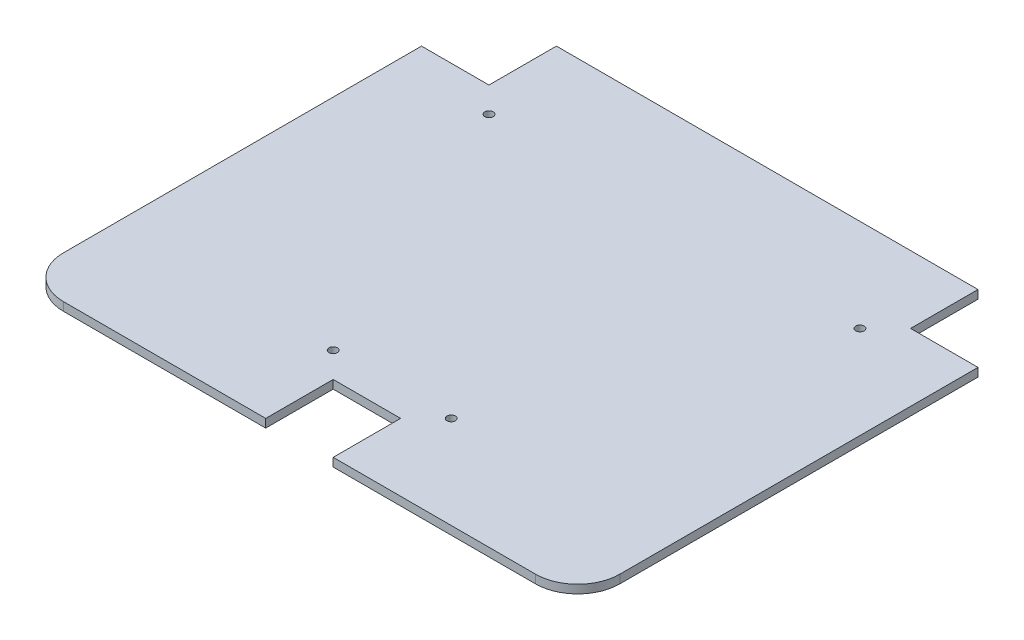
SolidWorks part; units mm, degrees
ref_plane "Plano frontal" through (0, 0, 0) normal (0, 0, 1) x (1, 0, 0)
ref_plane "Plano superior" through (0, 0, 0) normal (0, 1, 0) x (1, 0, 0)
ref_plane "Plano direito" through (0, 0, 0) normal (1, 0, 0) x (0, 0, -1)
sketch "Esboço1" plane through (0, 0, 0) normal (0, 1, 0) x (1, 0, 0)
  line L0 (516.2674, -155.797) -> (396.2674, -155.797)
  line L1 (371.2674, -130.797) -> (371.2674, 81.5882)
  line L2 (411.2674, 121.5882) -> (661.2674, 121.5882)
  line L3 (701.2674, -155.797) -> (411.2674, 81.5882) construction
  line L4 (371.2674, -155.797) -> (661.2674, 81.5882) construction
  line L5 (661.2674, 121.5882) -> (661.2674, 81.5882)
  line L6 (661.2674, 81.5882) -> (701.2674, 81.5882)
  line L7 (701.2674, 81.5882) -> (701.2674, -130.797)
  line L8 (676.2674, -155.797) -> (556.2674, -155.797)
  line L9 (556.2674, -115.797) -> (701.2674, -115.797) construction
  line L10 (516.2674, -115.797) -> (371.2674, -115.797) construction
  line L11 (516.2674, -115.797) -> (516.2674, 121.5882) construction
  line L14 (411.2674, 121.5882) -> (411.2674, 81.5882)
  line L15 (411.2674, 81.5882) -> (371.2674, 81.5882)
  line L17 (516.2674, -100.797) -> (516.2674, -115.797) construction
  line L22 (556.2674, -155.797) -> (556.2674, -115.797)
  line L23 (556.2674, -115.797) -> (516.2674, -115.797)
  line L24 (516.2674, -115.797) -> (516.2674, -155.797)
  arc A0 (371.2674, -130.797) -> (396.2674, -155.797) centre (396.2674, -130.797) ccw
  arc A1 (676.2674, -155.797) -> (701.2674, -130.797) centre (676.2674, -130.797) ccw
  dimension "D3" = 25
  dimension "D8" = 40
  dimension "D13" = 40
  dimension "D16" = 40
  dimension "D2" = 250
  dimension "D11" = 40
  dimension "D14" = 40
  dimension "D15" = 145
extrude "Ressalto-extrusão4" add sketch "Esboço1" along normal blind 5
sketch "Esboço2" plane through (0, 5, 0) normal (0, 1, 0) x (1, 0, 0)
  line L0 (661.2674, 81.5882) -> (661.2674, 66.5882) construction
  line L1 (411.2674, 81.5882) -> (426.2674, 81.5882) construction
  line L2 (426.2674, 81.5882) -> (426.2674, 66.5882) construction
  line L3 (426.2674, 66.5882) -> (411.2674, 66.5882) construction
  line L4 (411.2674, 66.5882) -> (411.2674, 81.5882) construction
  line L5 (556.2674, -115.797) -> (571.2674, -115.797) construction
  line L6 (571.2674, -115.797) -> (571.2674, -100.797) construction
  line L7 (571.2674, -100.797) -> (556.2674, -100.797) construction
  line L8 (556.2674, -100.797) -> (556.2674, -115.797) construction
  line L9 (516.2674, -115.797) -> (516.2674, -100.797) construction
  line L10 (516.2674, -100.797) -> (501.2674, -100.797) construction
  line L11 (501.2674, -100.797) -> (501.2674, -115.797) construction
  line L12 (501.2674, -115.797) -> (516.2674, -115.797) construction
  line L13 (661.2674, 66.5882) -> (646.2674, 66.5882) construction
  circle A0 centre (571.2674, -100.797) radius 2.5
  circle A1 centre (501.2674, -100.797) radius 2.5
  circle A2 centre (646.2674, 66.5882) radius 2.5
  circle A3 centre (426.2674, 66.5882) radius 2.5
  dimension "D1" = 15
  dimension "D6" = 15
  dimension "D2" = 15
  dimension "D3" = 15
  dimension "D4" = 15
  dimension "D5" = 15
  dimension "D7" = 15
  dimension "D8" = 15
extrude "Corte-extrusão1" cut sketch "Esboço2" against normal blind 5
